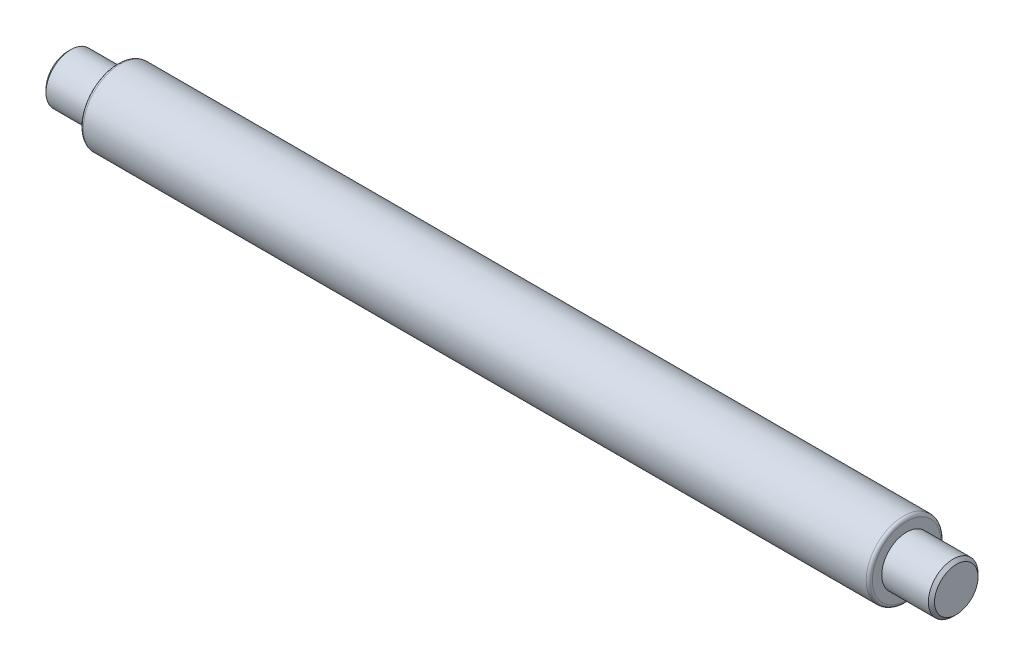
SolidWorks part; units mm, degrees
ref_plane "Front Plane" through (0, 0, 0) normal (0, 0, 1) x (1, 0, 0)
ref_plane "Top Plane" through (0, 0, 0) normal (0, 1, 0) x (1, 0, 0)
ref_plane "Right Plane" through (0, 0, 0) normal (1, 0, 0) x (0, 0, -1)
sketch "Sketch1" plane through (0, 0, 0) normal (0, 0, 1) x (1, 0, 0)
  line L0 (-39.7758, 0) -> (43.35, 0) construction
  line L1 (-35.75, 0) -> (-35.75, 2)
  line L2 (-35.75, 2) -> (-31.75, 2)
  line L3 (-31.75, 2) -> (-31.75, 3)
  line L4 (-31.75, 3) -> (31.75, 3)
  line L5 (31.75, 3) -> (31.75, 2)
  line L6 (31.75, 2) -> (35.75, 2)
  line L7 (35.75, 2) -> (35.75, 0)
  line L8 (35.75, 0) -> (-35.75, 0)
  point P7 (0, 3)
  point P12 (30.9842, 0)
  point P13 (-39.7758, 0)
  point P14 (43.35, 0)
  dimension "D1" = 4
  dimension "D2" = 63.5
  dimension "D3" = 4
  dimension "D4" = 6
revolve "Revolve1" add sketch "Sketch1" angle 360 about L0
cosmetic thread "Cosmetic Thread4" parameters "D2"=3.22
cosmetic thread "Cosmetic Thread5" parameters "D2"=3.22
chamfer "Chamfer3" distance 0.25 angle 45 2 edges at (-35.75, 0, 2) (35.75, 0, 2)
fillet "Fillet1" radius 0.25 2 edges at (-31.75, 0, 3) (31.75, 0, 3)
